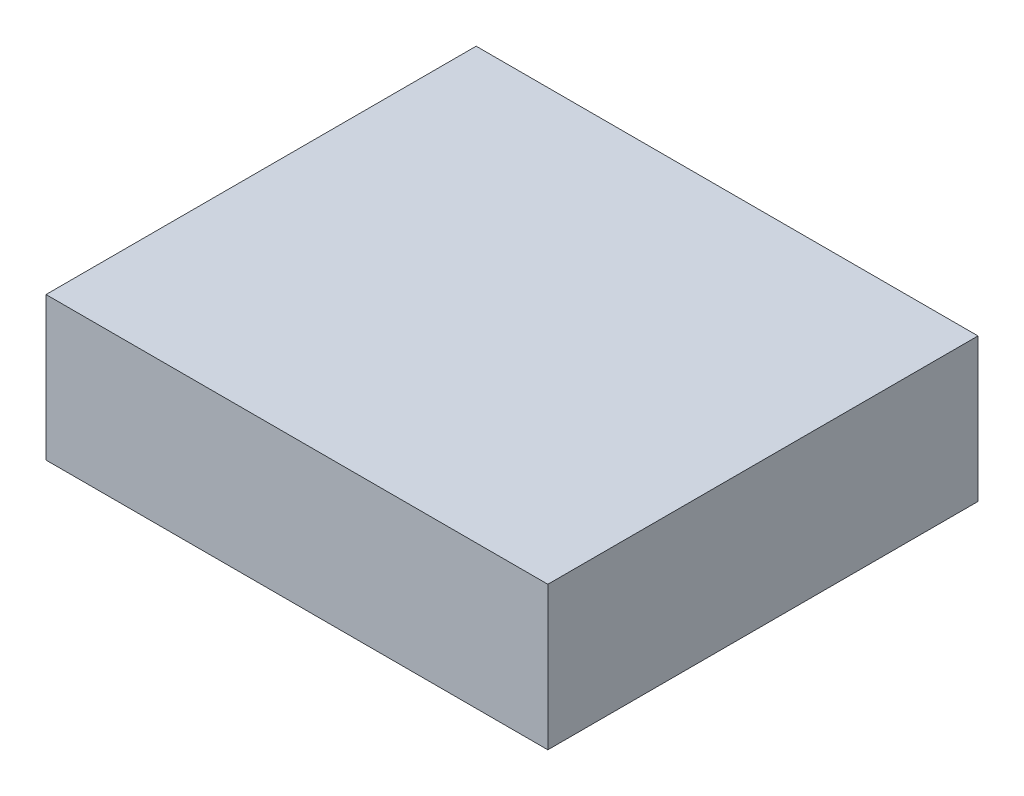
SolidWorks part; units mm, degrees
ref_plane "Front Plane" through (0, 0, 0) normal (0, 0, 1) x (1, 0, 0)
ref_plane "Top Plane" through (0, 0, 0) normal (0, 1, 0) x (1, 0, 0)
ref_plane "Right Plane" through (0, 0, 0) normal (1, 0, 0) x (0, 0, -1)
sketch "Sketch1" plane through (0, 0, 0) normal (0, 1, 0) x (1, 0, 0)
  line L1 (-74.6871, 30.7481) -> (103.1129, 30.7481)
  line L2 (-74.6871, 30.7481) -> (-74.6871, -121.6519)
  line L3 (-74.6871, -121.6519) -> (103.1129, -121.6519)
  line L4 (103.1129, 30.7481) -> (103.1129, -121.6519)
  dimension "D1" = 177.8
  dimension "D2" = 152.4
extrude "Boss-Extrude1" add sketch "Sketch1" along normal blind 50.8 contours L2 L1 L4 L3
